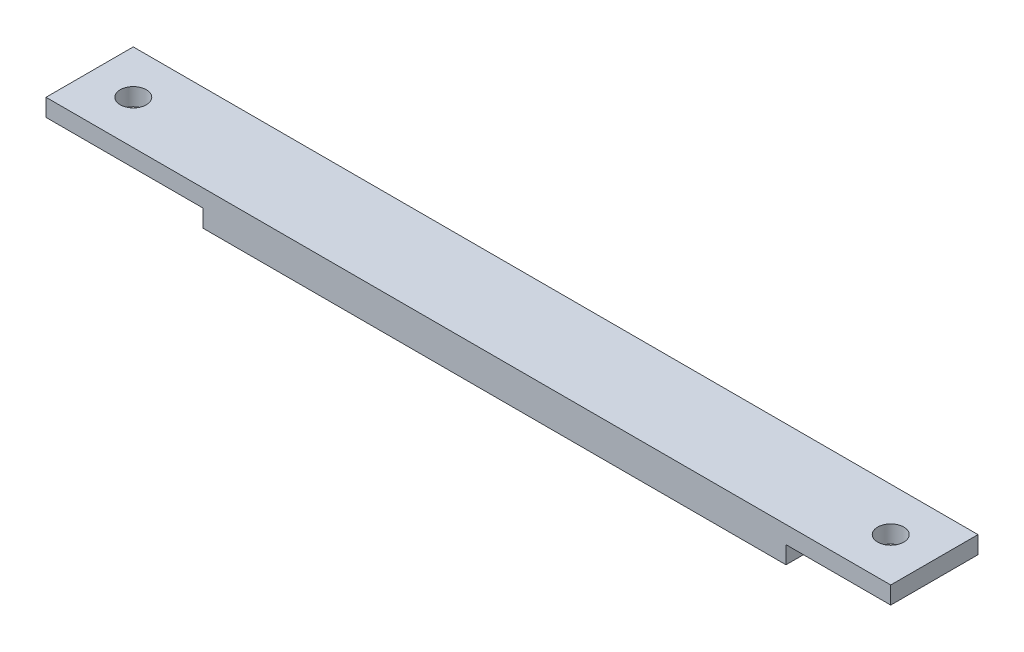
SolidWorks part; units mm, degrees
ref_plane "Alzado" through (0, 0, 0) normal (0, 0, 1) x (1, 0, 0)
ref_plane "Planta" through (0, 0, 0) normal (0, 1, 0) x (1, 0, 0)
ref_plane "Vista lateral" through (0, 0, 0) normal (1, 0, 0) x (0, 0, -1)
sketch "Croquis2" plane through (0, 0, 0) normal (0, 0, 1) x (1, 0, 0)
  line L1 (-48.4, 1) -> (48.4, 1)
  line L2 (-48.4, 1) -> (-48.4, -1)
  line L3 (-48.4, -1) -> (48.4, -1)
  line L4 (48.4, 1) -> (48.4, -1)
  line L5 (-48.4, 1) -> (48.4, -1) construction
  line L6 (-48.4, -1) -> (48.4, 1) construction
  point P0 (0, 0)
  dimension "D1" = 96.8
  dimension "D2" = 2
extrude "Saliente-Extruir2" add sketch "Croquis2" along normal blind 10
sketch "Croquis3" plane through (0, -1, 0) normal (0, -1, 0) x (1, 0, 0)
  line L0 (48.4, 10) -> (48.4, 0) construction
  line L1 (-30.4, 0) -> (36.4, 0)
  line L2 (-30.4, 0) -> (-30.4, 10)
  line L3 (-30.4, 10) -> (36.4, 10)
  line L4 (36.4, 0) -> (36.4, 10)
  line L5 (-30.4, 0) -> (36.4, 10) construction
  line L6 (-30.4, 10) -> (36.4, 0) construction
  line L7 (-48.4, 10) -> (-48.4, 0) construction
  line L8 (-48.4, 10) -> (48.4, 10) construction
  line L10 (-48.4, 0) -> (48.4, 0) construction
  point P0 (3, 5)
  dimension "D1" = 12
  dimension "D2" = 18
extrude "Saliente-Extruir3" add sketch "Croquis3" along normal blind 2
sketch "Croquis5" plane through (0, -1, 0) normal (0, -1, 0) x (1, 0, 0)
  line L0 (0, 0) -> (0, 21.0612) construction
  line L1 (36.4, 10) -> (48.4, 10) construction
  line L2 (48.4, 10) -> (48.4, 0) construction
  circle A0 centre (43.4, 5) radius 1.5
  circle A1 centre (-43.4, 5) radius 1.5
  dimension "D1" = 3
  dimension "D2" = 5
  dimension "D3" = 5
extrude "Cortar-Extruir1" cut sketch "Croquis5" against normal blind 2
